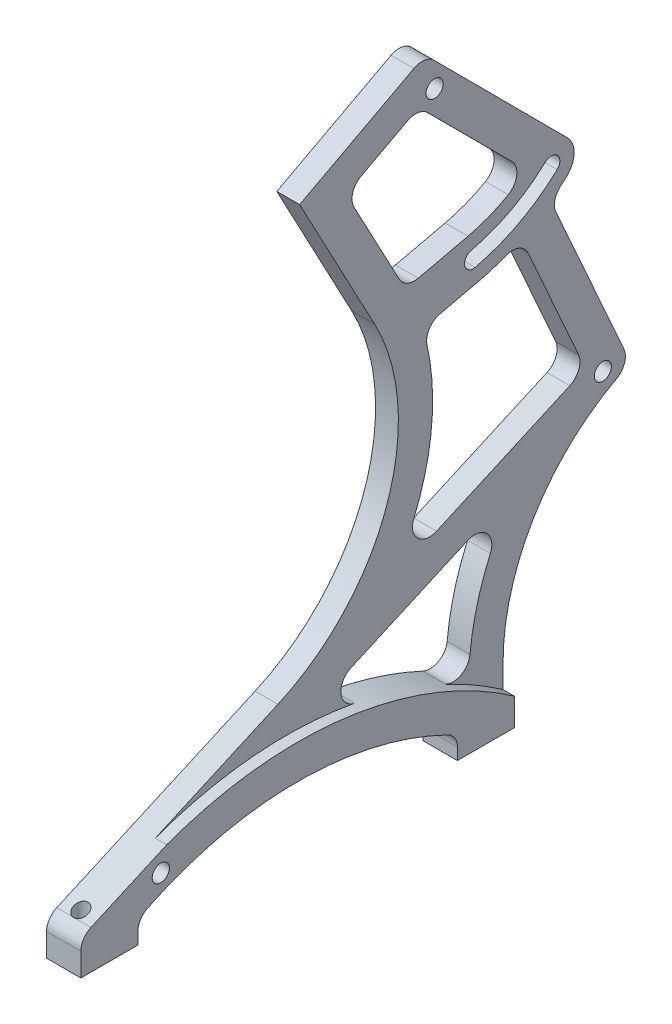
SolidWorks part; units mm, degrees
ref_plane "Front Plane" through (0, 0, 0) normal (0, 0, 1) x (1, 0, 0)
ref_plane "Top Plane" through (0, 0, 0) normal (0, 1, 0) x (1, 0, 0)
ref_plane "Right Plane" through (0, 0, 0) normal (1, 0, 0) x (0, 0, -1)
sketch "Sketch1" plane through (0, 0, 0) normal (1, 0, 0) x (0, 0, -1)
  line L0 (0, 0) -> (0, 6)
  line L1 (0, 6) -> (95.9223, 48.7073) construction
  line L2 (95.9223, 48.7073) -> (98.3627, 43.2261)
  line L3 (98.3627, 43.2261) -> (10, 3.8845) construction
  line L4 (66, 3.8845) -> (66, 0)
  line L5 (10, 3.8845) -> (10, 0)
  line L6 (10, 0) -> (0, 0)
  line L7 (66, 0) -> (76, 0)
  line L8 (76, 0) -> (76, 8.7905)
  line L9 (78.1749, 34.2379) -> (39.0321, 16.8104)
  line L10 (70, 8.542) -> (70, 8.7905)
  line L11 (70.7485, 72.7689) -> (64, 102) construction
  line L12 (64, 102) -> (84.46, 80.0594) construction
  line L13 (0, 6) -> (36.5418, 22.2695)
  line L14 (62.3411, 107.9134) -> (40.3467, 96.2188)
  line L15 (40.3467, 96.2188) -> (53.492, 71.4962)
  line L17 (62.3411, 107.9134) -> (87.2928, 82.8834)
  line L18 (64, 102) -> (78.0841, 75.5116) construction
  line L19 (46.9194, 83.8575) -> (78.3511, 100.5701) construction
  line L20 (84.3288, 74.7467) -> (95.9223, 48.7073)
  line L21 (56.2016, 31.0226) -> (90.441, 46.2669)
  line L22 (90.441, 46.2669) -> (79.1737, 71.5737)
  line L23 (80.1087, 81.5914) -> (61.2314, 100.5279)
  line L24 (61.2314, 100.5279) -> (48.4613, 93.7379)
  line L25 (48.4613, 93.7379) -> (58.8843, 74.135)
  line L26 (58.8843, 74.135) -> (69.8487, 76.6664)
  line L27 (61.9365, 66.6293) -> (71.6483, 68.8714)
  arc A0 (10, 3.8845) -> (66, 3.8845) centre (38, -49.1815) cw
  arc A1 (98.3627, 43.2261) -> (76, 8.7905) centre (113.6944, 8.7905) ccw
  arc A2 (39.0321, 16.8104) -> (70, 8.542) centre (38, -49.1815) cw
  arc A3 (70, 8.7905) -> (78.1749, 34.2379) centre (113.6944, 8.7905) cw
  circle A4 centre (64, 102) radius 1.5
  arc A5 (84.46, 80.0594) -> (70.7485, 72.7689) centre (64, 102) cw construction
  arc A6 (71.086, 71.3073) -> (85.4829, 78.9624) centre (64, 102) ccw
  arc A7 (70.4111, 74.2305) -> (83.437, 81.1564) centre (64, 102) ccw
  arc A8 (70.4111, 74.2305) -> (71.086, 71.3073) centre (70.7485, 72.7689) ccw
  arc A9 (85.4829, 78.9624) -> (83.437, 81.1564) centre (84.46, 80.0594) ccw
  arc A10 (71.6483, 68.8714) -> (79.1737, 71.5737) centre (64, 102) ccw
  arc A11 (53.492, 71.4962) -> (36.5418, 22.2695) centre (22.0645, 54.786) cw
  arc A12 (56.2016, 31.0226) -> (61.9365, 66.6293) centre (22.0645, 54.786) ccw
  circle A13 centre (70.7485, 72.7689) radius 4 construction
  arc A15 (69.8487, 76.6664) -> (80.1087, 81.5914) centre (64, 102) ccw
  arc A17 (87.2928, 82.8834) -> (87.1879, 77.134) centre (84.46, 80.0594) cw
  arc A18 (87.1879, 77.134) -> (84.3288, 74.7467) centre (64, 102) cw
  point P24 (78.0841, 75.5116)
  dimension "D8" = 60
  dimension "D9" = 6
  dimension "D10" = 6
  dimension "D11" = 3
  dimension "D12" = 30
  dimension "D14" = 64
  dimension "D21" = 6
  dimension "D24" = 6
  dimension "D25" = 1.5
  dimension "D26" = 4
  dimension "D32" = 4
  dimension "D33" = 8
  dimension "D1" = 6
  dimension "D2" = 24
  dimension "D3" = 105
  dimension "D4" = 10
  dimension "D5" = 10
  dimension "D6" = 6
  dimension "D7" = 56
  dimension "D13" = 102
  dimension "D15" = 62
  dimension "D16" = 30
  dimension "D17" = 6
  dimension "D19" = 28
  dimension "D20" = 3
  dimension "D22" = 40
  dimension "D27" = 12
  dimension "D28" = 6
  dimension "D29" = 6
  dimension "D31" = 6
extrude "Boss-Extrude1" add sketch "Sketch1" along normal blind 6
fillet "Fillet1" radius 3 17 edges at (3, 3.8845, -66) (3, 3.8845, -10) (3, 43.2261, -98.3627) (3, 16.8104, -39.0321) (3, 34.2379, -78.1749) (3, 8.542, -70) (3, 46.2669, -90.441) (3, 31.0226, -56.2016) (3, 81.5914, -80.1087) (3, 107.9134, -62.3411) (3, 100.5279, -61.2314) (3, 93.7379, -48.4613) (3, 74.135, -58.8843) (3, 6, 0) (3, 66.6293, -61.9365) (3, 74.7467, -84.3288) (3, 71.5737, -79.1737)
hole_wizard "Tap Drill for M3 Tap1" positions "Sketch4" profile "Sketch3" hole size "M3" standard "ISO"
sketch "Sketch4" plane through (0, 0, 0) normal (0, -1, 0) x (-1, 0, 0)
  line L0 (0, 0) -> (0, 10) construction
  line L1 (-6, 0) -> (0, 0) construction
  line L2 (-6, 76) -> (0, 76) construction
  point P0 (-3, 3)
  point P2 (-3, 70)
  dimension "D1" = 3
  dimension "D2" = 3
  dimension "D3" = 6
sketch "Sketch3" plane through (3, 0, -3) normal (1, 0, 0) x (0, 0, -1)
  line L0 (0, 0) -> (0, 8.7511)
  line L1 (0, 8.7511) -> (1.25, 8)
  line L2 (1.25, 8) -> (1.25, 0)
  line L5 (1.25, 0) -> (0, 0)
  line L10 (0, 8.7511) -> (-1.25, 8) construction
  line L11 (0, -6.35) -> (0, 107.95) construction
  dimension "Hole Dia." = 2.5
  dimension "Hole Depth" = 8
  dimension "Drill Angle" = 118
sketch "Sketch6" plane through (6, 0, 0) normal (1, 0, 0) x (0, 0, -1)
  line L1 (76, 0) -> (76, 8.7905) construction
  line L2 (0, 6) -> (0, 120)
  line L3 (0, 120) -> (100, 120)
  line L4 (100, 4.7814) -> (100, 120)
  line L5 (36.5418, 22.2695) -> (1.7798, 6.7924) construction
  line L6 (7.3812, 9.2863) -> (0, 6)
  line L7 (76, 4.7814) -> (100, 4.7814)
  arc A1 (7.3812, 9.2863) -> (76, 4.7814) centre (38, -49.1815) cw
  arc A3 (65.9503, 10.6079) -> (50.024, 15.7139) centre (38, -49.1815) ccw construction
  dimension "D1" = 120
  dimension "D3" = 100
extrude "Cut-Extrude1" cut sketch "Sketch6" against normal blind 2
sketch "Sketch7" plane through (6, 0, 0) normal (1, 0, 0) x (0, 0, -1)
  line L0 (15.0379, 12.6953) -> (1.7798, 6.7924) construction
  line L1 (87.7004, 45.0467) -> (64.345, 34.6482) construction
  line L2 (85.2713, 72.6297) -> (97.1875, 45.8656) construction
  circle A0 centre (14.0098, 8.9537) radius 1.5
  circle A1 centre (93.4883, 44.3398) radius 1.5
  dimension "D1" = 3
  dimension "D4" = 87
  dimension "D2" = 3
  dimension "D3" = 3
  dimension "D5" = 4
extrude "Cut-Extrude2" cut sketch "Sketch7" against normal up to next
equation "\"ˇ3\"=3.9176"
